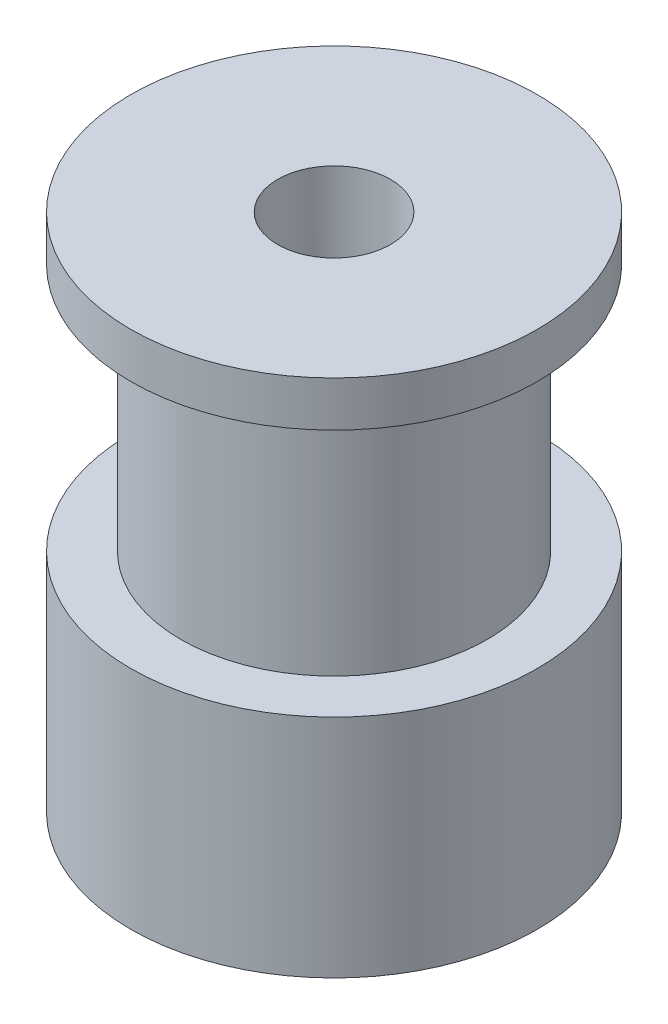
SolidWorks part; units mm, degrees
ref_plane "前视基准面" through (0, 0, 0) normal (0, 0, 1) x (1, 0, 0)
ref_plane "上视基准面" through (0, 0, 0) normal (0, 1, 0) x (1, 0, 0)
ref_plane "右视基准面" through (0, 0, 0) normal (1, 0, 0) x (0, 0, -1)
sketch "草图1" plane through (0, 0, 0) normal (0, 1, 0) x (1, 0, 0)
  circle A0 centre (0, 0) radius 9
  dimension "D1" = 18
extrude "凸台-拉伸1" add sketch "草图1" along normal blind 10
sketch "草图2" plane through (0, 10, 0) normal (0, 1, 0) x (1, 0, 0)
  circle A0 centre (0, 0) radius 6.78
  dimension "D1" = 13.56
extrude "凸台-拉伸2" add sketch "草图2" along normal blind 11
sketch "草图3" plane through (0, 21, 0) normal (0, 1, 0) x (1, 0, 0)
  circle A0 centre (0, 0) radius 9
  circle A1 centre (0, 0) radius 9 construction
extrude "凸台-拉伸3" add sketch "草图3" along normal blind 2
sketch "草图5" plane through (0, 0, 0) normal (0, -1, 0) x (1, 0, 0)
  circle A0 centre (0, 0) radius 2.5
  dimension "D1" = 5
extrude "切除-拉伸1" cut sketch "草图5" against normal through all
sketch "草图6" plane through (0, 0, 0) normal (0, 0, 1) x (1, 0, 0)
  line L0 (0, 6) -> (0, 0) construction
  circle A0 centre (0, 6) radius 1.5
  dimension "D2" = 3
  dimension "D1" = 6
extrude "切除-拉伸2" cut sketch "草图6" against normal through all
sketch "草图7" plane through (0, 0, 0) normal (1, 0, 0) x (0, 0, -1)
  line L0 (0, 6) -> (0, 0) construction
  circle A0 centre (0, 6) radius 1.5
  dimension "D1" = 3
  dimension "D2" = 6
extrude "切除-拉伸3" cut sketch "草图7" against normal through all
